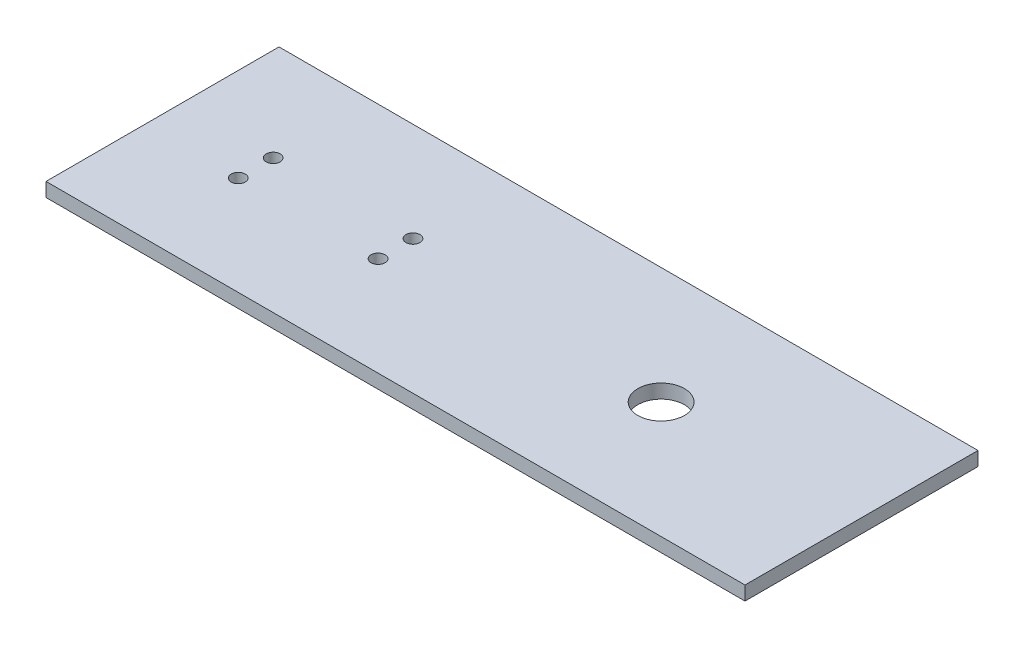
SolidWorks part; units mm, degrees
ref_plane "Front Plane" through (0, 0, 0) normal (0, 0, 1) x (1, 0, 0)
ref_plane "Top Plane" through (0, 0, 0) normal (0, 1, 0) x (1, 0, 0)
ref_plane "Right Plane" through (0, 0, 0) normal (1, 0, 0) x (0, 0, -1)
sketch "Sketch1" plane through (0, 0, 0) normal (0, 1, 0) x (1, 0, 0)
  line L1 (-75, -25) -> (75, -25)
  line L2 (-75, -25) -> (-75, 25)
  line L3 (-75, 25) -> (75, 25)
  line L4 (75, -25) -> (75, 25)
  line L5 (-75, -25) -> (75, 25) construction
  line L6 (-75, 25) -> (75, -25) construction
  point P0 (0, 0)
  dimension "D1" = 150
  dimension "D2" = 50
extrude "Boss-Extrude1" add sketch "Sketch1" along normal blind 3
sketch "Sketch2" plane through (0, 3, 0) normal (0, 1, 0) x (1, 0, 0)
  line L0 (-75, 0) -> (75, 0) construction
  line L1 (-75, 25) -> (-75, -25) construction
  line L2 (75, -25) -> (75, 25) construction
  line L3 (-55, 0) -> (-55, 3.75) construction
  line L4 (-40, 0) -> (-40, 17.7393) construction
  circle A0 centre (-55, 3.75) radius 1.5
  circle A1 centre (-55, -3.75) radius 1.5
  circle A2 centre (-25, -3.75) radius 1.5
  circle A3 centre (-25, 3.75) radius 1.5
  dimension "D1" = 3
  dimension "D2" = 7.5
  dimension "D3" = 30
  dimension "D4" = 20
extrude "Cut-Extrude1" cut sketch "Sketch2" against normal through all both and the other way through all
sketch "Sketch3" plane through (0, 3, 0) normal (0, 1, 0) x (1, 0, 0)
  line L0 (-25, -3.75) -> (-25, 3.75) construction
  line L1 (-25, 0) -> (32, 0) construction
  circle A0 centre (32, 0) radius 5
  dimension "D2" = 10
  dimension "D1" = 57
extrude "Cut-Extrude2" cut sketch "Sketch3" against normal through all
